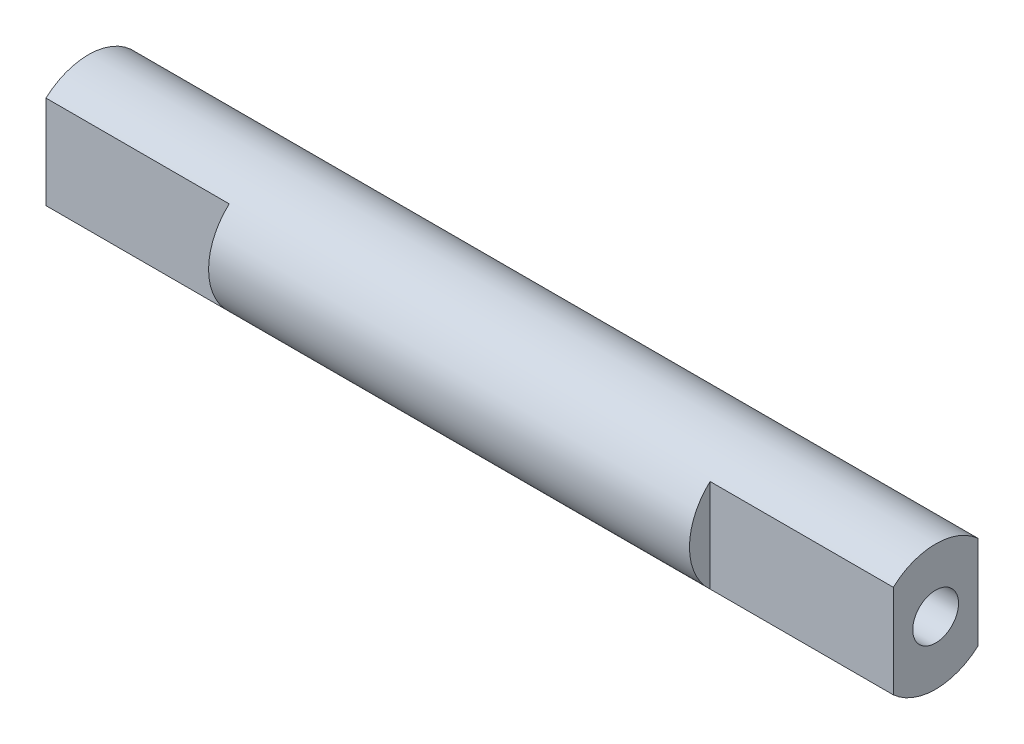
SolidWorks part; units mm, degrees
ref_plane "Front Plane" through (0, 0, 0) normal (0, 0, 1) x (1, 0, 0)
ref_plane "Top Plane" through (0, 0, 0) normal (0, 1, 0) x (1, 0, 0)
ref_plane "Right Plane" through (0, 0, 0) normal (1, 0, 0) x (0, 0, -1)
sketch "Sketch1" plane through (0, 0, 0) normal (1, 0, 0) x (0, 0, -1)
  circle A0 centre (0, 0) radius 2.75
  dimension "D1" = 5.5
extrude "Boss-Extrude1" add sketch "Sketch1" along normal mid plane 37
sketch "Sketch2" plane through (18.5, 0, 0) normal (1, 0, 0) x (0, 0, -1)
  line L0 (-1.85, 2.0347) -> (-1.85, -2.0347)
  line L1 (1.85, 2.0347) -> (1.85, -2.0347)
  arc A0 (-1.85, 2.0347) -> (-1.85, -2.0347) centre (0, 0) ccw
  arc A1 (1.85, -2.0347) -> (1.85, 2.0347) centre (0, 0) ccw
  circle A2 centre (0, 0) radius 2.75 construction
  dimension "D1" = 3.7
  dimension "D2" = 1.85
extrude "Cut-Extrude1" cut sketch "Sketch2" against normal blind 8
sketch "Sketch3" plane through (18.5, 0, 0) normal (1, 0, 0) x (0, 0, -1)
  circle A0 centre (0, 0) radius 1
  dimension "D1" = 2
extrude "Cut-Extrude2" cut sketch "Sketch3" against normal blind 6
mirror "Mirror1" about plane through (0, 0, 0) normal (1, 0, 0) of "Cut-Extrude1", "Cut-Extrude2"
